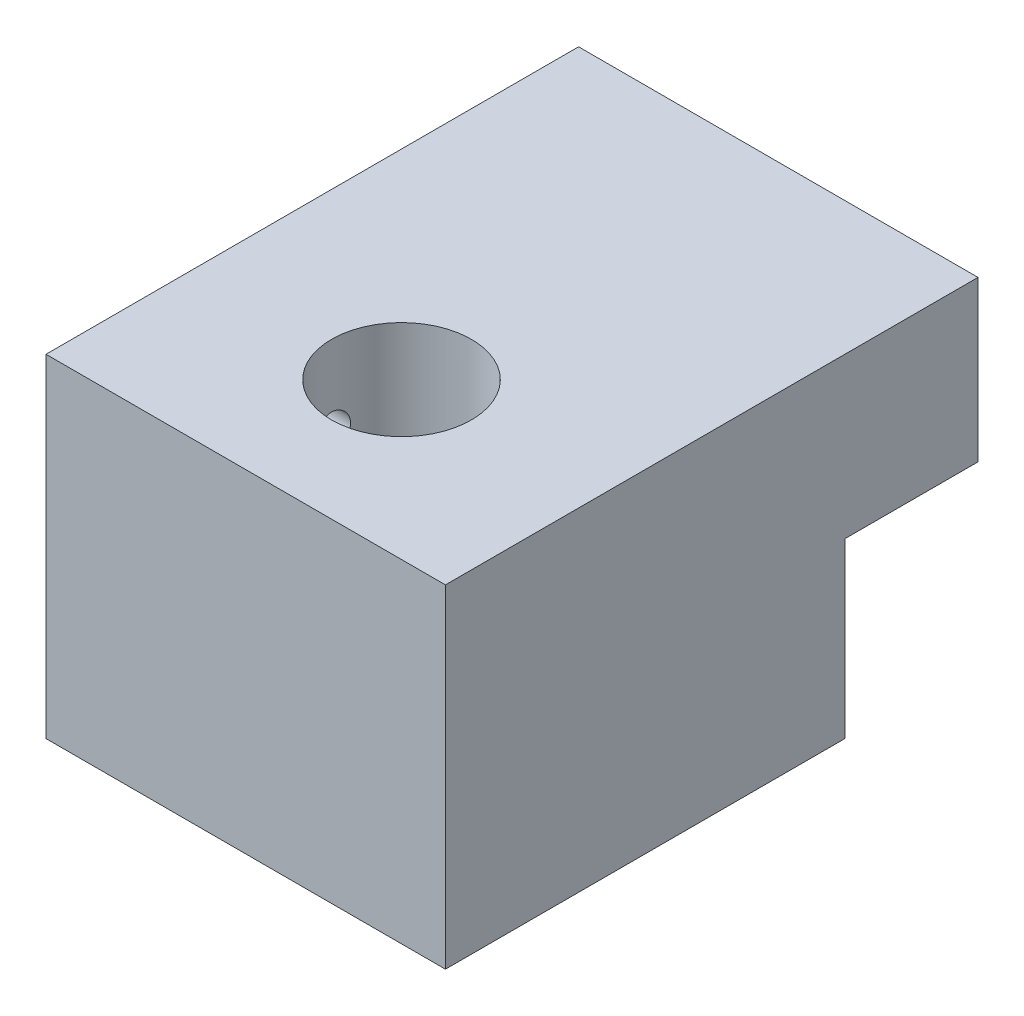
SolidWorks part; units mm, degrees
ref_plane "Front Plane" through (0, 0, 0) normal (0, 0, 1) x (1, 0, 0)
ref_plane "Top Plane" through (0, 0, 0) normal (0, 1, 0) x (1, 0, 0)
ref_plane "Right Plane" through (0, 0, 0) normal (1, 0, 0) x (0, 0, -1)
sketch "Sketch1" plane through (0, 0, 0) normal (0, 0, 1) x (1, 0, 0)
  line L1 (-15, 6) -> (15, 6)
  line L2 (-15, 6) -> (-15, -6)
  line L3 (-15, -6) -> (15, -6)
  line L4 (15, 6) -> (15, -6)
  line L5 (-15, 6) -> (15, -6) construction
  line L6 (-15, -6) -> (15, 6) construction
  point P0 (0, 0)
  dimension "D1" = 12
  dimension "D2" = 30
extrude "Boss-Extrude1" add sketch "Sketch1" along normal blind 40
sketch "Sketch2" plane through (0, 6, 0) normal (0, 1, 0) x (1, 0, 0)
  circle A0 centre (0, -28.3) radius 5.25
  dimension "D1" = 28.3
  dimension "D2" = 10.5
extrude "Cut-Extrude1" cut sketch "Sketch2" against normal through all
sketch "Sketch5" plane through (0, 0, 0) normal (0, 0, -1) x (-1, 0, 0)
  point P0 (10, 0)
  point P2 (-10, 0)
  dimension "D1" = 10
  dimension "D2" = 10
hole_wizard "#8-32 Tapped Hole1" positions "Sketch5" profile "Sketch6" tap size "#8-32" standard "ANSI Inch"
sketch "Sketch6" plane through (-10, 0, 0) normal (1, 0, 0) x (0, 1, 0)
  line L0 (0, 0) -> (0, 10.7631)
  line L1 (0, 10.7631) -> (1.27, 10)
  line L2 (1.27, 10) -> (1.27, 0)
  line L5 (1.27, 0) -> (0, 0)
  line L10 (0, 10.7631) -> (-1.27, 10) construction
  line L11 (0, -6.35) -> (0, 107.95) construction
  dimension "Tap Drill Dia." = 2.54
  dimension "Tap Drill Depth" = 10
  dimension "Drill Angle" = 118
cosmetic thread "Hole Thread1"
cosmetic thread "Hole Thread2"
sketch "Sketch10" plane through (0, -6, 0) normal (0, -1, 0) x (1, 0, 0)
  line L0 (15, 40) -> (15, 0) construction
  line L1 (-15, 40) -> (15, 40)
  line L2 (-15, 40) -> (-15, 10)
  line L3 (-15, 10) -> (15, 10)
  line L4 (15, 40) -> (15, 10)
  circle A0 centre (0, 28.3) radius 5.25 construction
  circle A1 centre (0, 28.3) radius 5.25
extrude "Boss-Extrude2" add sketch "Sketch10" along normal blind 13
sketch "Sketch9" plane through (-15, 0, 0) normal (-1, 0, 0) x (0, 0, 1)
  line L1 (0, 6) -> (0, -6) construction
  point P0 (28.3, 0)
  point P15 (28.3, -12)
  dimension "D1" = 28.3
  dimension "D2" = 12
hole_wizard "#8-32 Tapped Hole2" positions "Sketch9" profile "Sketch8" tap size "#8-32" standard "ANSI Inch"
sketch "Sketch8" plane through (-15, 0, 28.3) normal (0, 1, 0) x (0, 0, 1)
  line L0 (0, 0) -> (0, 11.4731)
  line L1 (0, 11.4731) -> (1.27, 10.71)
  line L2 (1.27, 10.71) -> (1.27, 0)
  line L5 (1.27, 0) -> (0, 0)
  line L10 (0, 11.4731) -> (-1.27, 10.71) construction
  line L11 (0, -6.35) -> (0, 107.95) construction
  dimension "Tap Drill Dia." = 2.54
  dimension "Tap Drill Depth" = 10.71
  dimension "Drill Angle" = 118
cosmetic thread "Hole Thread3"
cosmetic thread "Hole Thread4"
